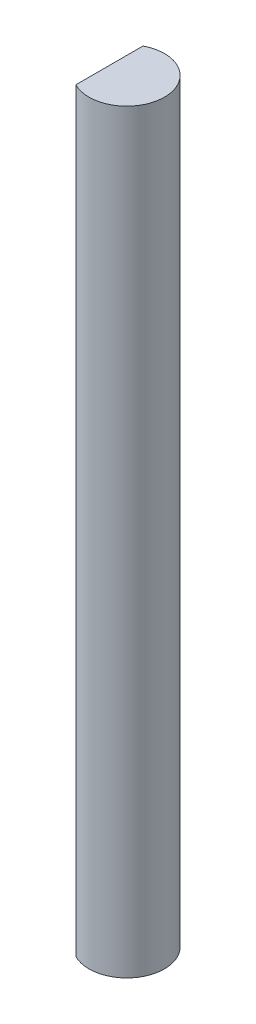
SolidWorks part; units mm, degrees
ref_plane "Front Plane" through (0, 0, 0) normal (0, 0, 1) x (1, 0, 0)
ref_plane "Top Plane" through (0, 0, 0) normal (0, 1, 0) x (1, 0, 0)
ref_plane "Right Plane" through (0, 0, 0) normal (1, 0, 0) x (0, 0, -1)
sketch "Sketch1" plane through (0, 0, 0) normal (0, 1, 0) x (1, 0, 0)
  line L0 (-4.5161, 3.3863) -> (-4.5161, -3.3863)
  line L1 (-4.5161, 0) -> (1.0402, 0)
  circle A0 centre (-2.7698, 0) radius 3.81
  dimension "D1" = 7.62
  dimension "D2" = 5.5562
extrude "Boss-Extrude1" add sketch "Sketch1" along normal blind 76.2 contours L1 A0 L0 | L0 A0 L1
